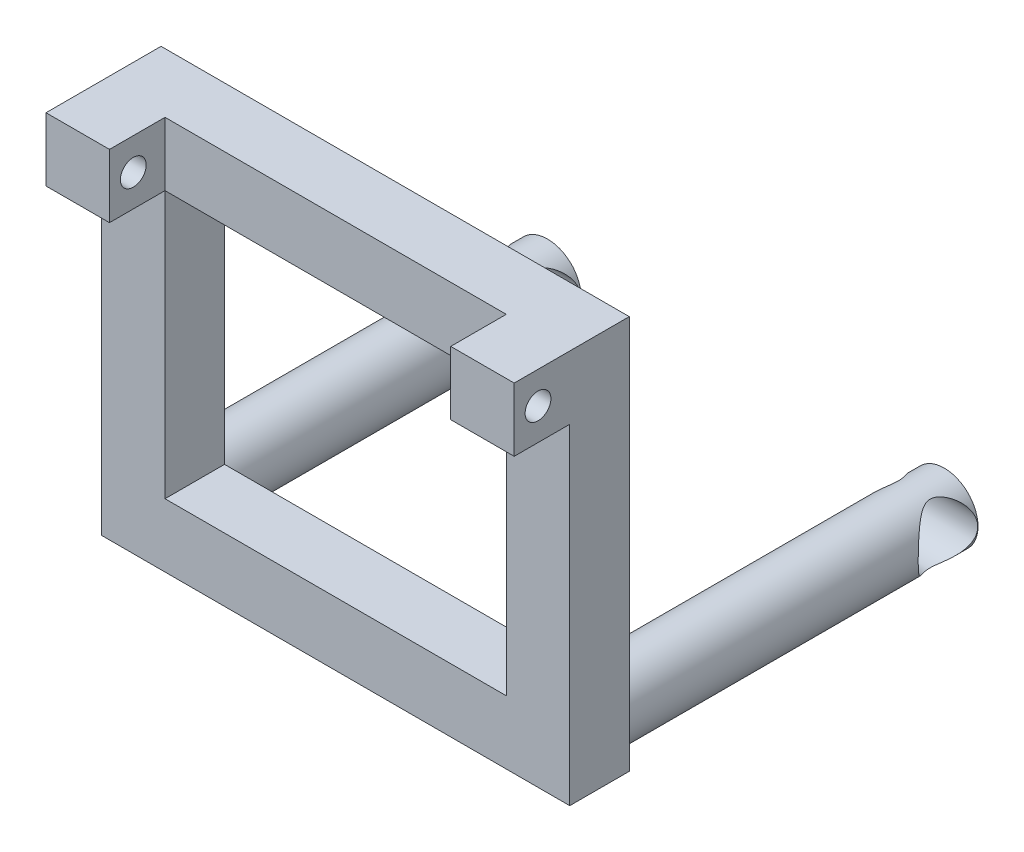
SolidWorks part; units mm, degrees
ref_plane "Front Plane" through (0, 0, 0) normal (0, 0, 1) x (1, 0, 0)
ref_plane "Top Plane" through (0, 0, 0) normal (0, 1, 0) x (1, 0, 0)
ref_plane "Right Plane" through (0, 0, 0) normal (1, 0, 0) x (0, 0, -1)
sketch "Sketch1" plane through (0, 0, 0) normal (0, 0, 1) x (1, 0, 0)
  line L0 (-796.3832, -7.0403) -> (-796.3832, -679.6151)
  line L1 (-956.3832, 152.9597) -> (223.6879, 152.9597)
  line L2 (-956.3832, 152.9597) -> (-956.3832, -839.6151)
  line L3 (-956.3832, -839.6151) -> (223.6879, -839.6151)
  line L4 (223.6879, 152.9597) -> (223.6879, -839.6151)
  line L9 (-796.3832, -679.6151) -> (63.6879, -679.6151)
  line L10 (63.6879, -7.0403) -> (63.6879, -679.6151)
  line L11 (-796.3832, -7.0403) -> (63.6879, -7.0403)
  dimension "D1" = 160
extrude "Boss-Extrude2" add sketch "Sketch1" along normal blind 150
sketch "Sketch2" plane through (0, 0, 150) normal (0, 0, 1) x (1, 0, 0)
  line L1 (-956.3832, 152.9597) -> (-796.3832, 152.9597)
  line L2 (-956.3832, 152.9597) -> (-956.3832, -7.0403)
  line L3 (-956.3832, -7.0403) -> (-796.3832, -7.0403)
  line L4 (-796.3832, 152.9597) -> (-796.3832, -7.0403)
  line L5 (63.6879, -7.0403) -> (223.6879, -7.0403)
  line L6 (63.6879, -7.0403) -> (63.6879, 152.9597)
  line L7 (63.6879, 152.9597) -> (223.6879, 152.9597)
  line L8 (223.6879, -7.0403) -> (223.6879, 152.9597)
extrude "Boss-Extrude3" add sketch "Sketch2" along normal blind 140
sketch "Sketch4" plane through (0, 0, 0) normal (0, 0, -1) x (-1, 0, 0)
  line L0 (956.3832, 152.9597) -> (956.3832, -839.6151) construction
  line L1 (-223.6879, -839.6151) -> (-223.6879, 152.9597) construction
  line L2 (956.3832, -839.6151) -> (-223.6879, -839.6151) construction
  circle A1 centre (-133.6879, -749.6151) radius 85
  circle A2 centre (866.3832, -749.6151) radius 85
  dimension "D1" = 170
  dimension "D4" = 170
  dimension "D5" = 90
  dimension "D2" = 90
  dimension "D3" = 90
  dimension "D6" = 90
extrude "Boss-Extrude4" add sketch "Sketch4" along normal blind 884
ref_plane "Plane1" through (233.6879, 0, 0) normal (1, 0, 0) x (0, 0, -1)
sketch "Sketch5" plane through (233.6879, 0, 0) normal (1, 0, 0) x (0, 0, -1)
  line L1 (0, -834.6151) -> (884, -834.6151) construction
  circle A0 centre (808.3432, -749.6151) radius 75
  dimension "D1" = 150
  dimension "D2" = 85
extrude "Cut-Extrude2" cut sketch "Sketch5" against normal through all
sketch "Sketch6" plane through (223.6879, 0, 0) normal (1, 0, 0) x (0, 0, -1)
  line L0 (-290, -7.0403) -> (-150, -7.0403) construction
  line L2 (-290, -7.0403) -> (-290, 152.9597) construction
  circle A0 centre (-230, 72.9597) radius 32.5
  dimension "D1" = 65
  dimension "D2" = 80
  dimension "D3" = 60
extrude "Cut-Extrude3" cut sketch "Sketch6" against normal through all
